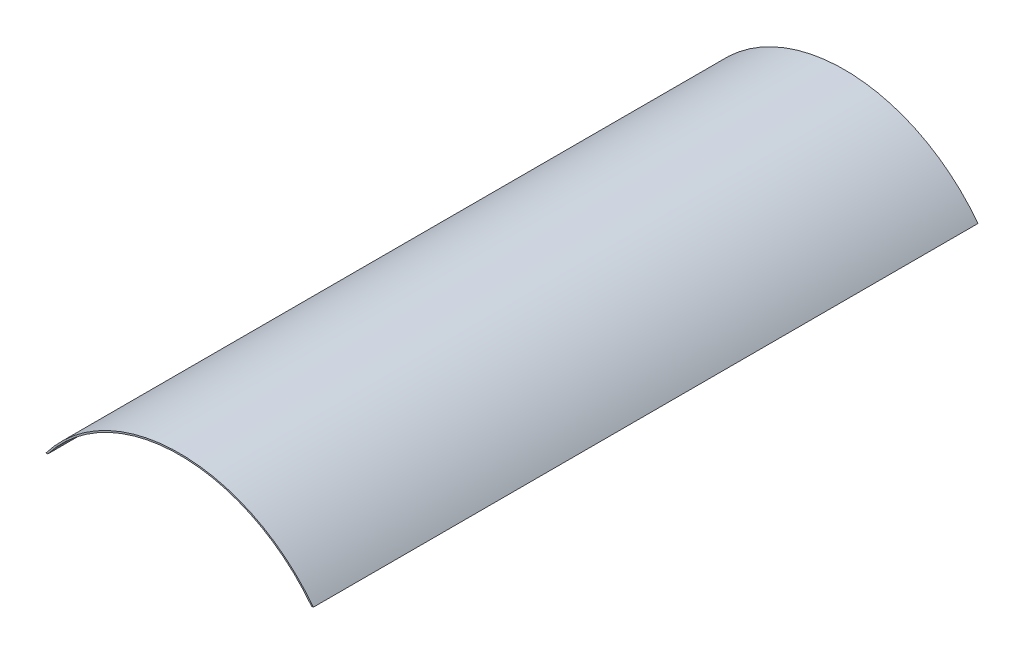
SolidWorks part; units mm, degrees
ref_plane "Спереди" through (0, 0, 0) normal (0, 0, 1) x (1, 0, 0)
ref_plane "Сверху" through (0, 0, 0) normal (0, 1, 0) x (1, 0, 0)
ref_plane "Справа" through (0, 0, 0) normal (1, 0, 0) x (0, 0, -1)
sketch "Эскиз1" plane through (0, 0, 0) normal (0, 0, 1) x (1, 0, 0)
  line L0 (-35.7, 0) -> (-36.2, 0)
  line L1 (36.2, 0) -> (35.7, 0)
  arc A0 (-35.7, 0) -> (35.7, 0) centre (0, -27.3954) cw
  arc A1 (-36.2, 0) -> (36.2, 0) centre (0, -27.3954) cw
  point P1 (-38.2798, 0)
  point P6 (43.4121, 0)
  dimension "D1" = 71.4
  dimension "D3" = 45
  dimension "D2" = 0.5
extrude "Бобышка-Вытянуть1" add sketch "Эскиз1" along normal blind 180
